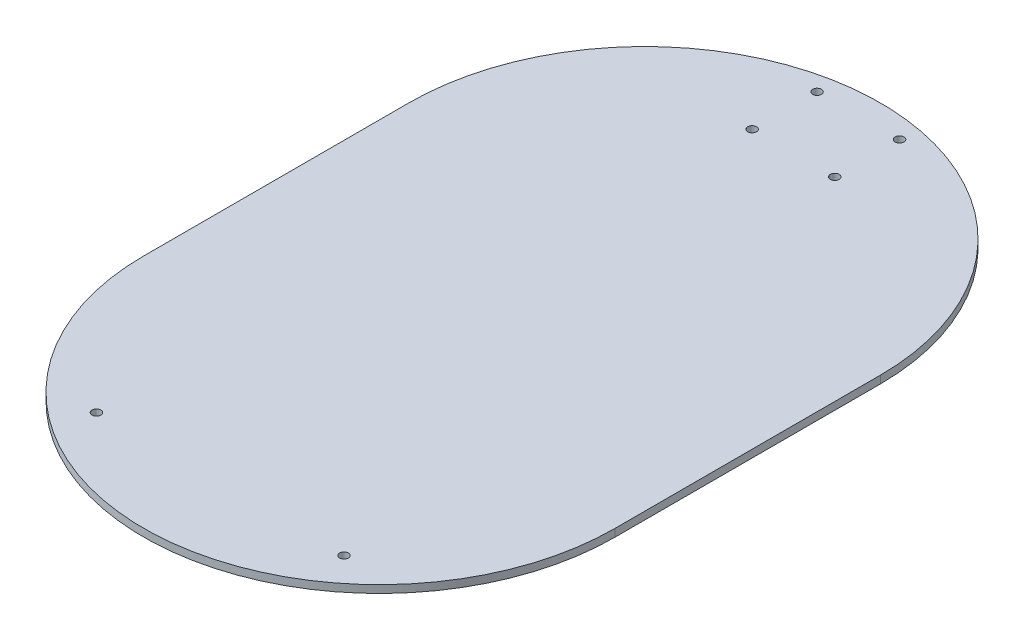
SolidWorks part; units mm, degrees
ref_plane "Płaszczyzna przednia" through (0, 0, 0) normal (0, 0, 1) x (1, 0, 0)
ref_plane "Płaszczyzna górna" through (0, 0, 0) normal (0, 1, 0) x (1, 0, 0)
ref_plane "Płaszczyzna prawa" through (0, 0, 0) normal (1, 0, 0) x (0, 0, -1)
sketch "Sketch2" plane through (0, 0, 0) normal (0, 1, 0) x (1, 0, 0)
  line L0 (0, -45) -> (0, 45) construction
  line L3 (-80, -45) -> (-80, 45)
  line L4 (80, -45) -> (80, 45)
  line L21 (0, -55) -> (0, 55) construction
  arc A4 (-80, -45) -> (80, -45) centre (0, -45) ccw
  arc A5 (80, 45) -> (-80, 45) centre (0, 45) ccw
  circle A6 centre (14, 117.5) radius 1.5
  circle A7 centre (14, 95.5) radius 1.5
  circle A8 centre (-14, 95.5) radius 1.5
  circle A9 centre (-14, 117.5) radius 1.5
  circle A10 centre (42, -99) radius 1.5
  circle A11 centre (-42, -99) radius 1.5
  point P3 (0, 0)
  point P8 (0, 125)
  point P9 (0, -125)
  dimension "D19" = 3
  dimension "D20" = 3
  dimension "D23" = 3
  dimension "D1" = 250
  dimension "D2" = 160
  dimension "D3" = 99
  dimension "D18" = 22
  dimension "D21" = 14
  dimension "D22" = 7.5
  dimension "D25" = 42
extrude "Boss-Extrude2" add sketch "Sketch2" along normal blind 2.6
